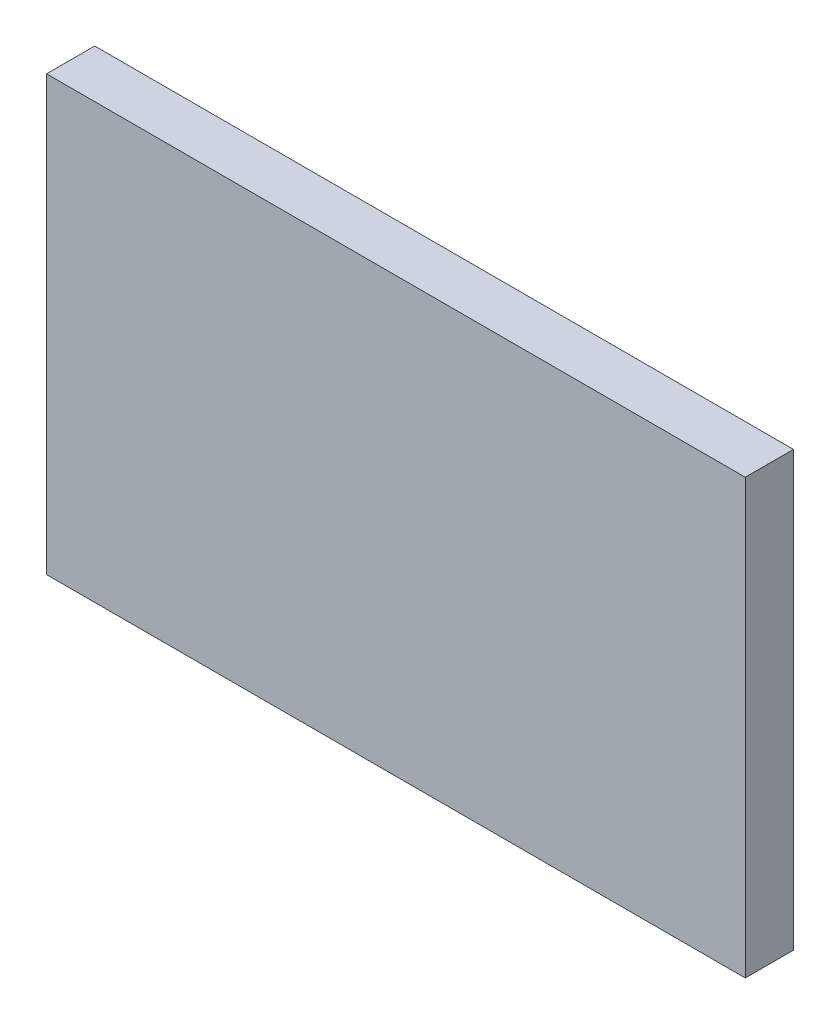
SolidWorks part; units mm, degrees
ref_plane "Front Plane" through (0, 0, 0) normal (0, 0, 1) x (1, 0, 0)
ref_plane "Top Plane" through (0, 0, 0) normal (0, 1, 0) x (1, 0, 0)
ref_plane "Right Plane" through (0, 0, 0) normal (1, 0, 0) x (0, 0, -1)
sketch "Sketch1" plane through (0, 0, 0) normal (0, 0, 1) x (1, 0, 0)
  line L1 (-46.0375, 28.575) -> (46.0375, 28.575)
  line L2 (-46.0375, 28.575) -> (-46.0375, -28.575)
  line L3 (-46.0375, -28.575) -> (46.0375, -28.575)
  line L4 (46.0375, 28.575) -> (46.0375, -28.575)
  line L5 (-46.0375, 28.575) -> (46.0375, -28.575) construction
  line L6 (-46.0375, -28.575) -> (46.0375, 28.575) construction
  point P0 (0, 0)
  dimension "D1" = 57.15
  dimension "D2" = 92.075
extrude "Boss-Extrude1" add sketch "Sketch1" along normal blind 6.35
